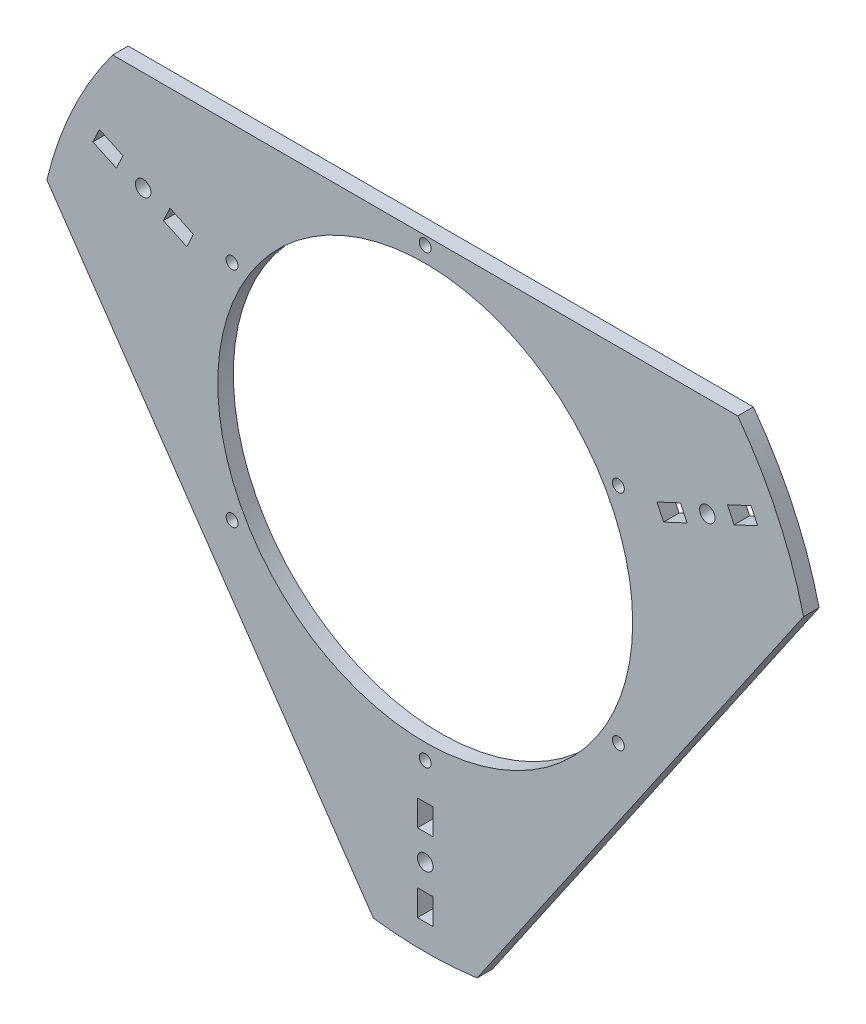
SolidWorks part; units mm, degrees
ref_plane "Front Plane" through (0, 0, 0) normal (0, 0, 1) x (1, 0, 0)
ref_plane "Top Plane" through (0, 0, 0) normal (0, 1, 0) x (1, 0, 0)
ref_plane "Right Plane" through (0, 0, 0) normal (1, 0, 0) x (0, 0, -1)
sketch "Sketch1" plane through (0, 0, 0) normal (0, 0, 1) x (1, 0, 0)
  line L0 (0, 0) -> (0, -75) construction
  line L1 (0, 0) -> (67.9731, 31.6964) construction
  line L2 (0, 0) -> (-67.9731, 31.6964) construction
  line L3 (-72.939, 17.4614) -> (-10, -74.3303)
  line L4 (10, -74.3303) -> (72.939, 17.4614)
  line L5 (60.2605, 44.6506) -> (-60.2605, 44.6506)
  circle A0 centre (0, 0) radius 40
  circle A1 centre (0, 0) radius 75 construction
  circle A2 centre (0, 0) radius 60 construction
  arc A3 (-72.939, 17.4614) -> (-60.2605, 44.6506) centre (0, 0) cw
  arc A4 (60.2605, 44.6506) -> (72.939, 17.4614) centre (0, 0) cw
  arc A5 (10, -74.3303) -> (-10, -74.3303) centre (0, 0) cw
  circle A6 centre (0, 0) radius 43 construction
  circle A7 centre (0, -43) radius 1.15
  circle A8 centre (-37.2391, -21.5) radius 1.15
  circle A9 centre (-37.2391, 21.5) radius 1.15
  circle A10 centre (0, 43) radius 1.15
  circle A11 centre (37.2391, 21.5) radius 1.15
  circle A12 centre (37.2391, -21.5) radius 1.15
  point P29 (0, 0)
  line B0 (0, -55) -> (0, -65) construction
  line B1 (1.5, -55) -> (1.5, -50)
  line B2 (1.5, -55) -> (-1.5, -55)
  line B3 (-1.5, -55) -> (-1.5, -50)
  line B4 (1.5, -50) -> (-1.5, -50)
  line B5 (1.5, -65) -> (1.5, -70)
  line B6 (1.5, -65) -> (-1.5, -65)
  line B7 (-1.5, -65) -> (-1.5, -70)
  line B8 (1.5, -70) -> (-1.5, -70)
  circle B9 centre (0, -60) radius 1.5
  line B10 (49.8469, 23.244) -> (58.91, 27.4702) construction
  line B11 (49.213, 24.6035) -> (44.6815, 22.4904)
  line B12 (49.213, 24.6035) -> (50.4809, 21.8845)
  line B13 (50.4809, 21.8845) -> (45.9493, 19.7715)
  line B14 (44.6815, 22.4904) -> (45.9493, 19.7715)
  line B15 (58.2761, 28.8296) -> (62.8076, 30.9427)
  line B16 (58.2761, 28.8296) -> (59.5439, 26.1107)
  line B17 (59.5439, 26.1107) -> (64.0755, 28.2238)
  line B18 (62.8076, 30.9427) -> (64.0755, 28.2238)
  circle B19 centre (54.3785, 25.3571) radius 1.5
  line B20 (-58.91, 27.4702) -> (-49.8469, 23.244) construction
  line B21 (-58.2761, 28.8296) -> (-62.8076, 30.9427)
  line B22 (-58.2761, 28.8296) -> (-59.5439, 26.1107)
  line B23 (-59.5439, 26.1107) -> (-64.0755, 28.2238)
  line B24 (-62.8076, 30.9427) -> (-64.0755, 28.2238)
  line B25 (-49.213, 24.6035) -> (-44.6815, 22.4904)
  line B26 (-49.213, 24.6035) -> (-50.4809, 21.8845)
  line B27 (-50.4809, 21.8845) -> (-45.9493, 19.7715)
  line B28 (-44.6815, 22.4904) -> (-45.9493, 19.7715)
  circle B29 centre (-54.3785, 25.3571) radius 1.5
  dimension "D1" = 80
  dimension "D2" = 150
  dimension "D4" = 120
  dimension "D7" = 2.3
  dimension "D8" = 86
  dimension "D3" = 115
  dimension "D5" = 15
  dimension "D6" = 10
  dimension "D9" = 6
sketch_block_instance "Trou M3 plots 3mm-1"
sketch_block "Trou M3 plots 3mm" parameters "D2"=3, "D1"=3, "D3"=5, "D4"=10
sketch_block_instance "Trou M3 plots 3mm-2"
sketch_block_instance "Trou M3 plots 3mm-3"
extrude "Boss-Extrude1" add sketch "Sketch1" along normal blind 3
